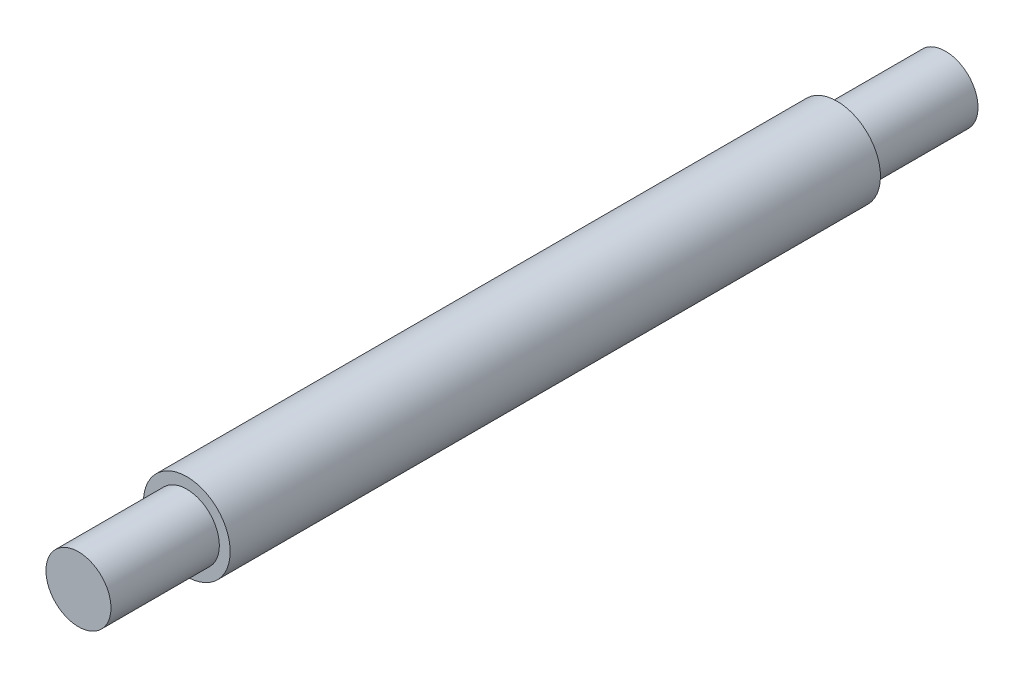
SolidWorks part; units mm, degrees
ref_plane "前视基准面" through (0, 0, 0) normal (0, 0, 1) x (1, 0, 0)
ref_plane "上视基准面" through (0, 0, 0) normal (0, 1, 0) x (1, 0, 0)
ref_plane "右视基准面" through (0, 0, 0) normal (1, 0, 0) x (0, 0, -1)
ref_plane "基准面4" through (0, 0, 526.9141) normal (0, 0, -1) x (-1, 0, 0)
sketch "草图1" plane through (0, 0, 526.9141) normal (0, 0, -1) x (-1, 0, 0)
  circle A0 centre (340.2875, -246.1546) radius 4
extrude "凸台-拉伸1" add sketch "草图1" along normal mid plane 60
sketch "草图2" plane through (0, 0, 496.9141) normal (0, 0, -1) x (-1, 0, 0)
  circle A0 centre (340.2875, -246.1546) radius 3
extrude "凸台-拉伸2" add sketch "草图2" along normal blind 10
sketch "草图3" plane through (0, 0, 556.9141) normal (0, 0, 1) x (1, 0, 0)
  circle A0 centre (-340.2875, -246.1546) radius 3
extrude "凸台-拉伸3" add sketch "草图3" along normal blind 10
